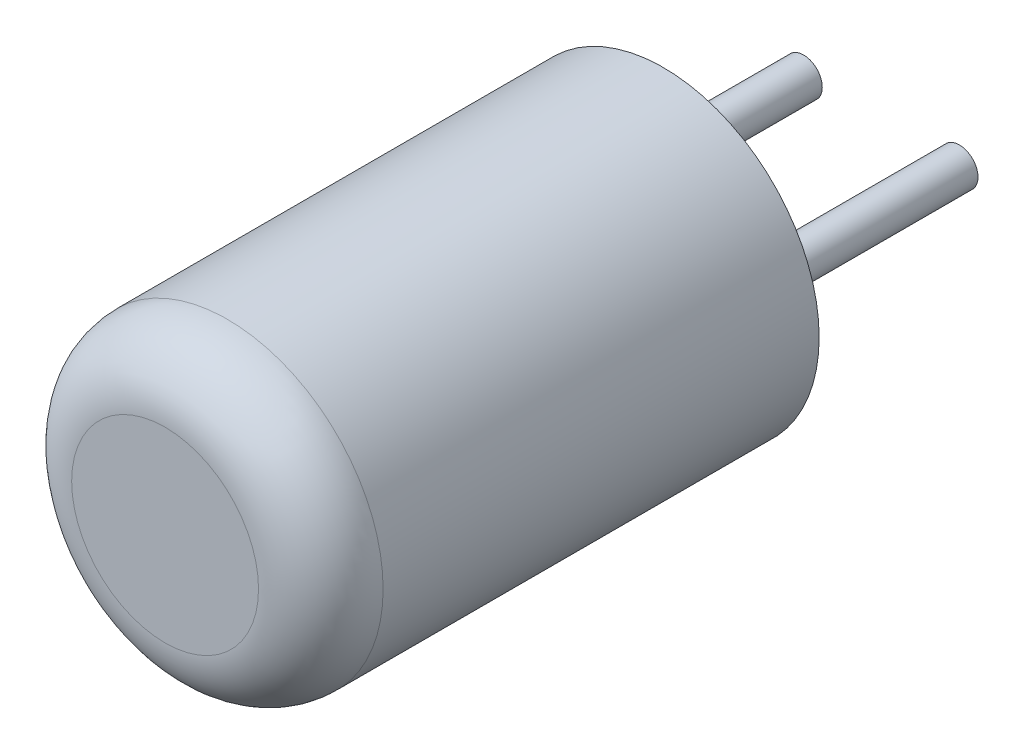
SolidWorks part; units mm, degrees
ref_plane "Спереди" through (0, 0, 0) normal (0, 0, 1) x (1, 0, 0)
ref_plane "Сверху" through (0, 0, 0) normal (0, 1, 0) x (1, 0, 0)
ref_plane "Справа" through (0, 0, 0) normal (1, 0, 0) x (0, 0, -1)
sketch "Эскиз1" plane through (0, 0, 0) normal (0, 0, 1) x (1, 0, 0)
  circle A0 centre (0, 0) radius 2.5
  dimension "D1" = 5
extrude "Вытянуть1" add sketch "Эскиз1" along normal blind 8
sketch "Эскиз2" plane through (0, 0, 0) normal (0, 0, -1) x (-1, 0, 0)
  line L0 (-8.813, 0) -> (9.6479, 0) construction
  line L1 (0, 0) -> (0, 4.6268) construction
  circle A0 centre (-1.25, 0) radius 0.3
  circle A1 centre (1.25, 0) radius 0.3
  dimension "D1" = 2.5
  dimension "D2" = 0.6
extrude "Вытянуть2" add sketch "Эскиз2" along normal blind 3.5
fillet "Скругление1" radius 1 1 edges at (2.5, 0, 8)
